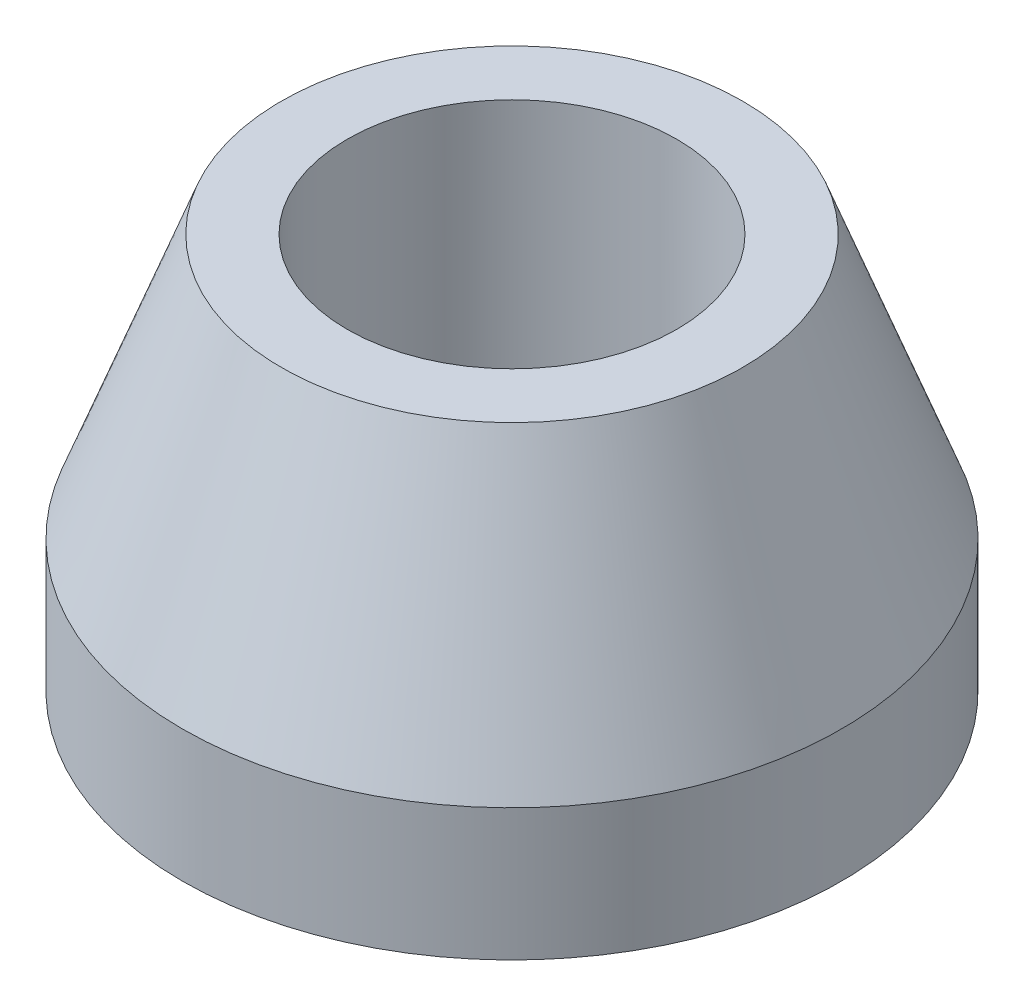
SolidWorks part; units mm, degrees
ref_plane "前基準面" through (0, 0, 0) normal (0, 0, 1) x (1, 0, 0)
ref_plane "上基準面" through (0, 0, 0) normal (0, 1, 0) x (1, 0, 0)
ref_plane "右基準面" through (0, 0, 0) normal (1, 0, 0) x (0, 0, -1)
sketch "草圖1" plane through (0, 0, 0) normal (0, 0, 1) x (1, 0, 0)
  line L0 (25, 0) -> (50, 0)
  line L1 (50, 0) -> (50, 20)
  line L2 (50, 20) -> (35, 60)
  line L3 (35, 60) -> (25, 60)
  line L4 (25, 60) -> (25, 0)
  line L5 (0, 0) -> (0, 60) construction
  point P8 (0, 0)
  point P9 (0, 0)
  point P10 (0, 0)
  point P11 (0, 0)
  dimension "D1" = 60
  dimension "D2" = 20
  dimension "D3" = 10
  dimension "D4" = 25
  dimension "D5" = 50
  dimension "D6" = 25
revolve "旋轉1" add sketch "草圖1" angle 360 about L5
sketch "草圖2" plane through (0, 0, 0) normal (0, 0, 1) x (1, 0, 0)
  line L0 (0, 0) -> (0, 10) construction
  circle A0 centre (0, 10) radius 5
  dimension "D1" = 10
  dimension "D2" = 10
extrude "除料-伸長1" cut sketch "草圖2" against normal through all
